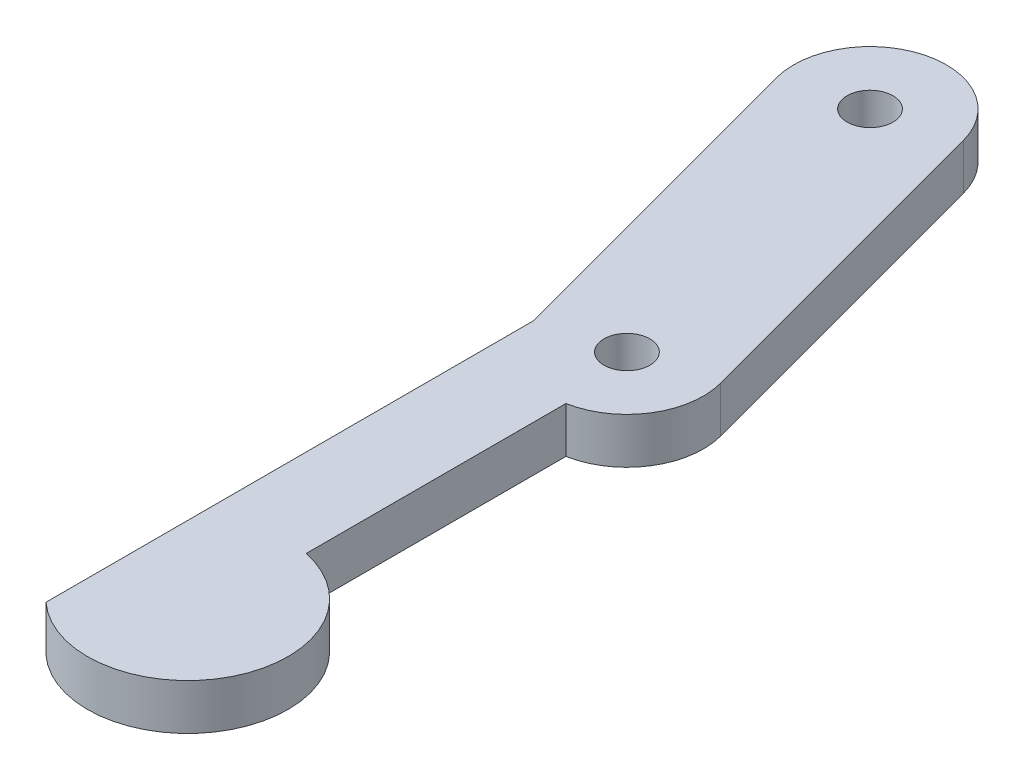
SolidWorks part; units mm, degrees
ref_plane "Front Plane" through (0, 0, 0) normal (0, 0, 1) x (1, 0, 0)
ref_plane "Top Plane" through (0, 0, 0) normal (0, 1, 0) x (1, 0, 0)
ref_plane "Right Plane" through (0, 0, 0) normal (1, 0, 0) x (0, 0, -1)
sketch "Sketch1" plane through (0, 0, 0) normal (0, 1, 0) x (1, 0, 0)
  line L0 (0, 0) -> (5.8234, -21.7333) construction
  line L1 (4.8296, 1.2941) -> (10.6531, -20.4392) construction
  line L2 (-4.8296, -1.2941) -> (0.9938, -23.0274) construction
  line L3 (0, 0) -> (14.6819, 0) construction
  line L4 (0.9938, -23.0274) -> (0.9938, -43.6479)
  line L5 (0.9938, -43.6479) -> (6.7438, -43.6479) construction
  line L6 (6.7438, -43.6479) -> (6.7438, -26.6479)
  line L7 (0.9938, -23.0274) -> (-4.8296, -1.2941)
  line L8 (-4.8296, -1.2941) -> (4.8296, 1.2941) construction
  line L9 (4.8296, 1.2941) -> (10.6531, -20.4392)
  line L10 (0.9938, -43.6479) -> (0.9938, -54.9211)
  arc A0 (4.8296, 1.2941) -> (-4.8296, -1.2941) centre (0, 0) ccw construction
  arc A1 (0.9938, -23.0274) -> (10.6531, -20.4392) centre (5.8234, -21.7333) ccw construction
  arc A2 (0.9938, -54.9211) -> (6.7438, -43.6479) centre (5.4317, -50.0817) ccw
  arc A3 (-4.8296, -1.2941) -> (4.8296, 1.2941) centre (0, 0) cw
  arc A4 (10.6531, -20.4392) -> (6.7438, -26.6479) centre (5.8234, -21.7333) cw
  circle A5 centre (0, 0) radius 1.5
  circle A6 centre (5.8234, -21.7333) radius 1.5
  point P3 (2.9117, -10.8667)
  point P23 (5.4317, -56.6479)
  dimension "D3" = 5
  dimension "D1" = 22.5
  dimension "D2" = 75
  dimension "D4" = 5.75
  dimension "D5" = 17
  dimension "D6" = 30
extrude "Boss-Extrude1" add sketch "Sketch1" along normal blind 3 contours A4 L9 A3 L7 L4 L10 A2 L6 A6 A5
